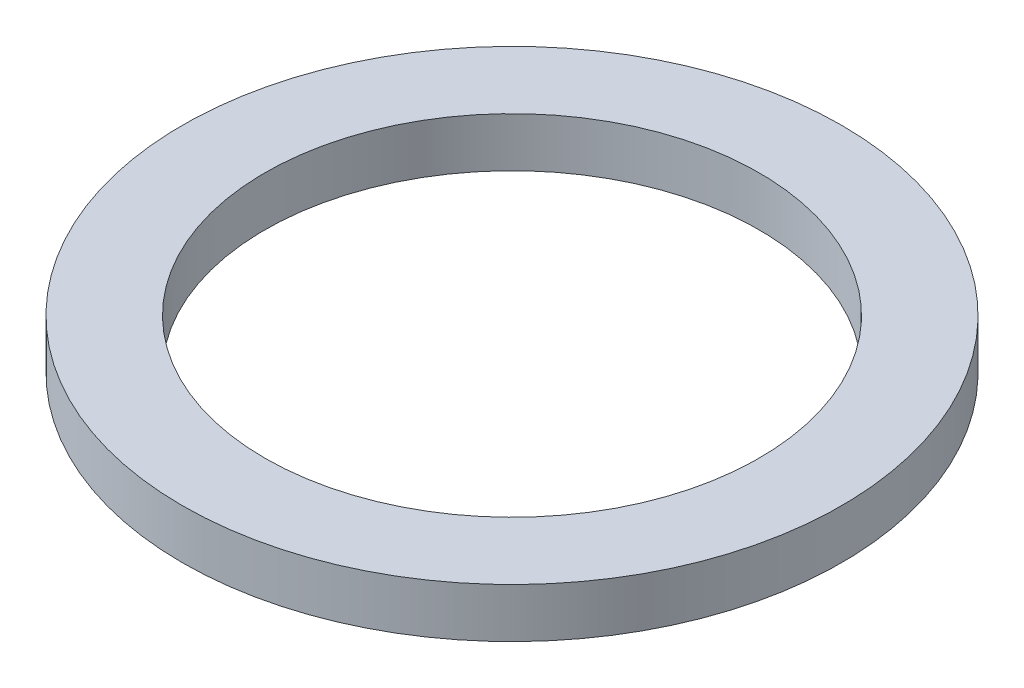
SolidWorks part; units mm, degrees
ref_plane "Front Plane" through (0, 0, 0) normal (0, 0, 1) x (1, 0, 0)
ref_plane "Top Plane" through (0, 0, 0) normal (0, 1, 0) x (1, 0, 0)
ref_plane "Right Plane" through (0, 0, 0) normal (1, 0, 0) x (0, 0, -1)
sketch "Sketch1" plane through (0, 0, 0) normal (0, 1, 0) x (1, 0, 0)
  circle A0 centre (0, 0) radius 10
  circle A1 centre (0, 0) radius 7.5
  dimension "D1" = 20
  dimension "D2" = 15
extrude "Boss-Extrude1" add sketch "Sketch1" along normal blind 1.5
